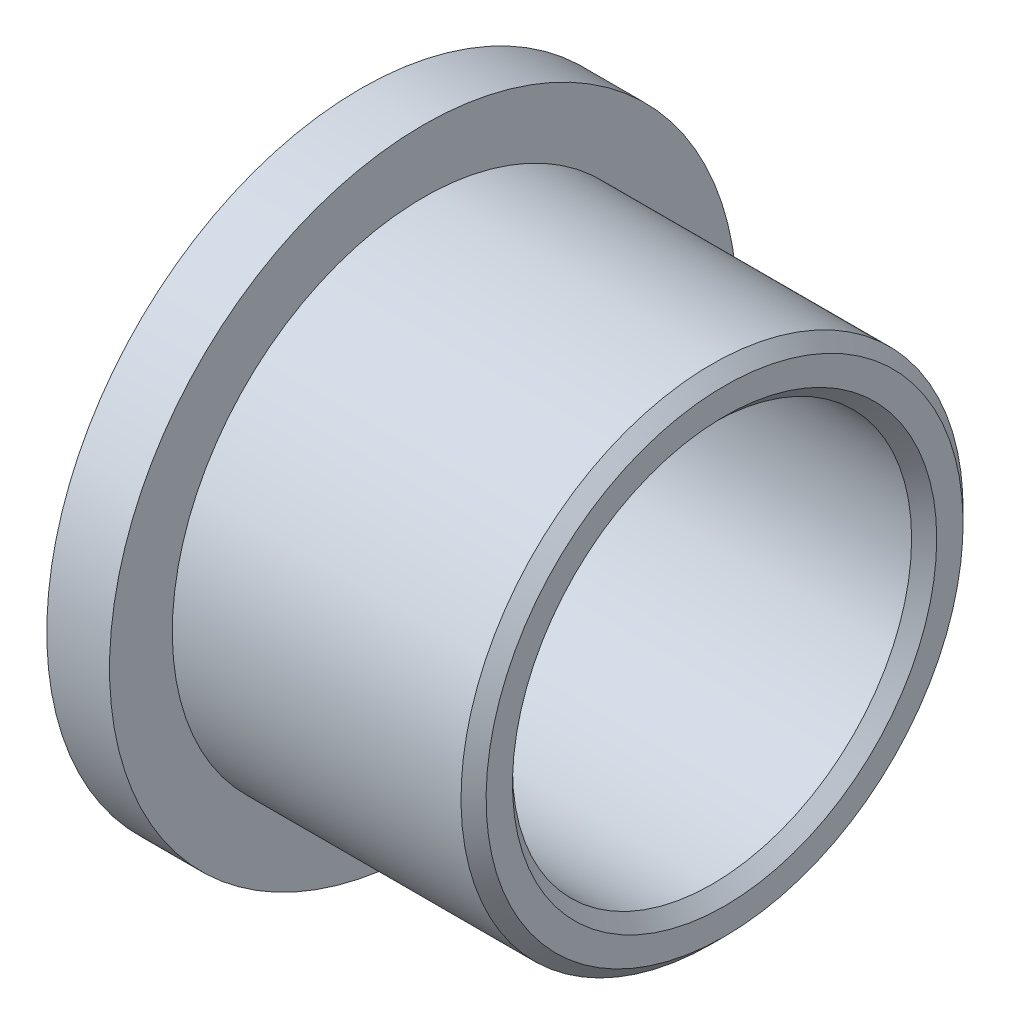
SolidWorks part; units mm, degrees
material "Laiton"
ref_plane "Plan de face" through (0, 0, 0) normal (0, 0, 1) x (1, 0, 0)
ref_plane "Plan de dessus" through (0, 0, 0) normal (0, 1, 0) x (1, 0, 0)
ref_plane "Plan de droite" through (0, 0, 0) normal (1, 0, 0) x (0, 0, -1)
sketch "Esquisse1" plane through (0, 0, 0) normal (0, 0, 1) x (1, 0, 0)
  line L0 (-19.5398, 0) -> (19.5398, 0) construction
  line L1 (0, 0) -> (0, 12.5)
  line L2 (0, 12.5) -> (2.5, 12.5)
  line L3 (2.5, 12.5) -> (2.5, 10)
  line L4 (2.5, 10) -> (14.5, 10)
  line L5 (14.5, 10) -> (14.5, 0)
  line L6 (14.5, 0) -> (0, 0)
  point P3 (0, 0)
  dimension "D1" = 25
  dimension "D2" = 20
  dimension "D3" = 2.5
  dimension "D4" = 14.5
revolve "Révolution1" add sketch "Esquisse1" angle 360 about L0
hole_wizard "Diamètre du perçage Ø0.15 (0.15)1" positions "Esquisse2" profile "Esquisse3" hole size "Ø0.15" standard "Ansi Metric" end condition through all
sketch "Esquisse2" plane through (14.5, 0, 0) normal (1, 0, 0) x (0, 0, -1)
  point P0 (0, 0)
sketch "Esquisse3" plane through (14.5, 0, 0) normal (0, 1, 0) x (0, 0, -1)
  line L0 (0, 0) -> (0, 14.5)
  line L1 (0, 14.5) -> (7.95, 14.5)
  line L2 (7.95, 14.5) -> (7.95, 0)
  line L5 (7.95, 0) -> (0, 0)
  line L11 (0, -6.35) -> (0, 107.95) construction
  dimension "Diamètre du perçage jusqu'au prochain" = 15.9
  dimension "Profondeur du perçage jusqu'au prochain" = 14.5
chamfer "Chanfrein1" distance 0.5 angle 45 3 edges at (14.5, -10, 0) (14.5, 0, -7.95) (0, 0, -7.95)
